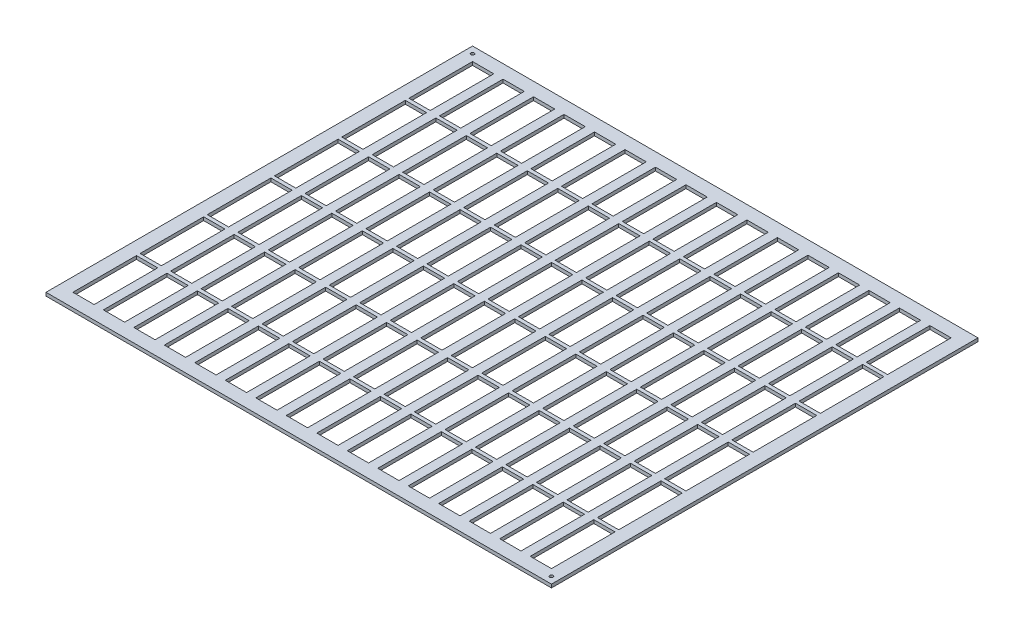
SolidWorks part; units mm, degrees
ref_plane "Front" through (0, 0, 0) normal (0, 0, 1) x (1, 0, 0)
ref_plane "Top" through (0, 0, 0) normal (0, 1, 0) x (1, 0, 0)
ref_plane "Right" through (0, 0, 0) normal (1, 0, 0) x (0, 0, -1)
sketch "Sketch1" plane through (0, 0, 0) normal (0, 1, 0) x (1, 0, 0)
  line L0 (0, -76.0537) -> (0, -227.7466) construction
  line L5 (-238.9187, -201.6125) -> (238.9188, -201.6125)
  line L6 (-238.9187, -201.6125) -> (-238.9187, 201.6125)
  line L7 (-238.9187, 201.6125) -> (238.9188, 201.6125)
  line L8 (238.9188, -201.6125) -> (238.9188, 201.6125)
  line L9 (-238.9187, -201.6125) -> (238.9188, 201.6125) construction
  line L10 (-238.9187, 201.6125) -> (238.9188, -201.6125) construction
  line L11 (55.3206, 0) -> (102.8784, 0) construction
  point P0 (0, 0)
  dimension "D1" = 477.8375
  dimension "D2" = 403.225
extrude "Boss-Extrude1" add sketch "Sketch1" along normal blind 3.175
sketch "Sketch2" plane through (0, 0, 0) normal (0, 1, 0) x (1, 0, 0)
  line L1 (-226.2187, 188.9125) -> (-206.1187, 188.9125)
  line L2 (-226.2187, 188.9125) -> (-226.2187, 128.8125)
  line L3 (-226.2187, 128.8125) -> (-206.1187, 128.8125)
  line L4 (-206.1187, 188.9125) -> (-206.1187, 128.8125)
  line L8 (206.1188, -128.8125) -> (226.2188, -128.8125) construction
  line L9 (206.1188, -128.8125) -> (206.1188, -188.9125) construction
  line L10 (206.1188, -188.9125) -> (226.2188, -188.9125) construction
  line L11 (226.2188, -128.8125) -> (226.2188, -188.9125) construction
  line L12 (-226.2187, -188.9125) -> (226.2188, -188.9125)
  line L13 (226.2188, -188.9125) -> (226.2188, 188.9125)
  line L14 (226.2188, 188.9125) -> (-226.2187, 188.9125)
  line L15 (-226.2187, 188.9125) -> (-226.2187, -188.9125)
  line L16 (-226.2187, -188.9125) -> (226.2188, -188.9125) construction
  line L17 (226.2188, -188.9125) -> (226.2188, 188.9125) construction
  line L18 (226.2188, 188.9125) -> (-226.2187, 188.9125) construction
  line L19 (-226.2187, 188.9125) -> (-226.2187, -188.9125) construction
  line L20 (216.1688, -128.8125) -> (216.1688, -188.9125) construction
  line L21 (206.1188, -158.8625) -> (226.2188, -158.8625) construction
  dimension "D1" = 60.1
  dimension "D2" = 20.1
  dimension "D3" = 12.7
extrude "Cut-Extrude1" cut sketch "Sketch2" along normal through all
pattern_linear "LPattern2" count 16 spacing 28.8225 along (1, 0, 0) count 6 spacing 63.545 along (0, 0, 1) of "Cut-Extrude1"
sketch "Sketch4" plane through (0, 0, 0) normal (0, 1, 0) x (1, 0, 0)
  line L0 (-238.9187, -201.6125) -> (238.9188, -201.6125) construction
  line L1 (238.9188, -201.6125) -> (238.9188, 201.6125) construction
  line L2 (238.9188, 201.6125) -> (-238.9187, 201.6125) construction
  line L3 (-238.9187, 201.6125) -> (-238.9187, -201.6125) construction
  circle A0 centre (-232.5687, 195.2625) radius 1.5875
  circle A1 centre (232.5688, -195.2625) radius 1.5875
  dimension "D3" = 3.175
  dimension "D6" = 3.175
  dimension "D1" = 6.35
  dimension "D2" = 6.35
  dimension "D4" = 6.35
  dimension "D5" = 6.35
extrude "Cut-Extrude2" cut sketch "Sketch4" along normal through all
sketch "v1" plane through (0, 0, 0) normal (0, 1, 0) x (1, 0, 0)
  line L0 (238.9188, -201.6125) -> (238.9188, 201.6125) construction
  line L9 (-238.9187, -201.6125) -> (238.9188, -201.6125) construction
  line L10 (-238.9187, 201.6125) -> (-238.9187, -201.6125) construction
  line L11 (238.9188, 201.6125) -> (-238.9187, 201.6125) construction
  line L12 (238.9188, -201.6125) -> (238.9188, 201.6125)
  line L13 (-238.9187, -201.6125) -> (238.9188, -201.6125)
  line L14 (-238.9187, 201.6125) -> (-238.9187, -201.6125)
  line L15 (238.9188, 201.6125) -> (-238.9187, 201.6125)
  line L16 (-206.1187, 128.8125) -> (-206.1187, 188.9125) construction
  line L17 (-206.1187, 188.9125) -> (-226.2187, 188.9125) construction
  line L18 (-226.2187, 128.8125) -> (-206.1187, 128.8125) construction
  line L19 (-226.2187, 188.9125) -> (-226.2187, 128.8125) construction
  line L20 (-226.2187, 128.8125) -> (-206.1187, 128.8125)
  line L21 (-206.1187, 188.9125) -> (-226.2187, 188.9125)
  line L22 (-206.1187, 128.8125) -> (-206.1187, 188.9125)
  line L23 (-226.2187, 188.9125) -> (-226.2187, 128.8125)
  line L24 (-180.7187, 188.9125) -> (-200.8187, 188.9125)
  line L25 (-226.2187, 188.9125) -> (-206.1187, 188.9125)
  line L26 (-226.2187, 188.9125) -> (-226.2187, 128.8125)
  line L27 (-226.2187, 128.8125) -> (-206.1187, 128.8125)
  line L28 (-206.1187, 188.9125) -> (-206.1187, 128.8125)
  line L29 (-200.8187, 188.9125) -> (-200.8187, 128.8125)
  line L30 (-200.8187, 128.8125) -> (-180.7187, 128.8125)
  line L31 (-180.7187, 128.8125) -> (-180.7187, 188.9125)
  line L32 (-155.3187, 188.9125) -> (-175.4187, 188.9125)
  line L33 (-175.4187, 188.9125) -> (-175.4187, 128.8125)
  line L34 (-175.4187, 128.8125) -> (-155.3187, 128.8125)
  line L35 (-155.3187, 128.8125) -> (-155.3187, 188.9125)
  line L36 (-129.9187, 188.9125) -> (-150.0187, 188.9125)
  line L37 (-150.0187, 188.9125) -> (-150.0187, 128.8125)
  line L38 (-150.0187, 128.8125) -> (-129.9187, 128.8125)
  line L39 (-129.9187, 128.8125) -> (-129.9187, 188.9125)
  line L40 (-104.5187, 188.9125) -> (-124.6187, 188.9125)
  line L41 (-124.6187, 188.9125) -> (-124.6187, 128.8125)
  line L42 (-124.6187, 128.8125) -> (-104.5187, 128.8125)
  line L43 (-104.5187, 128.8125) -> (-104.5187, 188.9125)
  line L44 (-79.1187, 188.9125) -> (-99.2187, 188.9125)
  line L45 (-99.2187, 188.9125) -> (-99.2187, 128.8125)
  line L46 (-99.2187, 128.8125) -> (-79.1187, 128.8125)
  line L47 (-79.1187, 128.8125) -> (-79.1187, 188.9125)
  line L48 (-53.7187, 188.9125) -> (-73.8187, 188.9125)
  line L49 (-73.8187, 188.9125) -> (-73.8187, 128.8125)
  line L50 (-73.8187, 128.8125) -> (-53.7187, 128.8125)
  line L51 (-53.7187, 128.8125) -> (-53.7187, 188.9125)
  line L52 (-28.3187, 188.9125) -> (-48.4187, 188.9125)
  line L53 (-48.4187, 188.9125) -> (-48.4187, 128.8125)
  line L54 (-48.4187, 128.8125) -> (-28.3187, 128.8125)
  line L55 (-28.3187, 128.8125) -> (-28.3187, 188.9125)
  line L56 (-2.9187, 188.9125) -> (-23.0187, 188.9125)
  line L57 (-23.0187, 188.9125) -> (-23.0187, 128.8125)
  line L58 (-23.0187, 128.8125) -> (-2.9187, 128.8125)
  line L59 (-2.9187, 128.8125) -> (-2.9187, 188.9125)
  line L60 (22.4813, 188.9125) -> (2.3813, 188.9125)
  line L61 (2.3813, 188.9125) -> (2.3813, 128.8125)
  line L62 (2.3813, 128.8125) -> (22.4813, 128.8125)
  line L63 (22.4813, 128.8125) -> (22.4813, 188.9125)
  line L64 (47.8813, 188.9125) -> (27.7813, 188.9125)
  line L65 (27.7813, 188.9125) -> (27.7813, 128.8125)
  line L66 (27.7813, 128.8125) -> (47.8813, 128.8125)
  line L67 (47.8813, 128.8125) -> (47.8813, 188.9125)
  line L68 (73.2813, 188.9125) -> (53.1813, 188.9125)
  line L69 (53.1813, 188.9125) -> (53.1813, 128.8125)
  line L70 (53.1813, 128.8125) -> (73.2813, 128.8125)
  line L71 (73.2813, 128.8125) -> (73.2813, 188.9125)
  line L72 (98.6813, 188.9125) -> (78.5813, 188.9125)
  line L73 (78.5813, 188.9125) -> (78.5813, 128.8125)
  line L74 (78.5813, 128.8125) -> (98.6813, 128.8125)
  line L75 (98.6813, 128.8125) -> (98.6813, 188.9125)
  line L76 (124.0813, 188.9125) -> (103.9813, 188.9125)
  line L77 (103.9813, 188.9125) -> (103.9813, 128.8125)
  line L78 (103.9813, 128.8125) -> (124.0813, 128.8125)
  line L79 (124.0813, 128.8125) -> (124.0813, 188.9125)
  line L80 (149.4813, 188.9125) -> (129.3813, 188.9125)
  line L81 (129.3813, 188.9125) -> (129.3813, 128.8125)
  line L82 (129.3813, 128.8125) -> (149.4813, 128.8125)
  line L83 (149.4813, 128.8125) -> (149.4813, 188.9125)
  line L84 (174.8813, 188.9125) -> (154.7813, 188.9125)
  line L85 (154.7813, 188.9125) -> (154.7813, 128.8125)
  line L86 (154.7813, 128.8125) -> (174.8813, 128.8125)
  line L87 (174.8813, 128.8125) -> (174.8813, 188.9125)
  line L88 (-180.7187, 125.4125) -> (-200.8187, 125.4125)
  line L89 (-200.8187, 125.4125) -> (-200.8187, 65.3125)
  line L90 (-200.8187, 65.3125) -> (-180.7187, 65.3125)
  line L91 (-180.7187, 65.3125) -> (-180.7187, 125.4125)
  line L92 (-155.3187, 125.4125) -> (-175.4187, 125.4125)
  line L93 (-175.4187, 125.4125) -> (-175.4187, 65.3125)
  line L94 (-175.4187, 65.3125) -> (-155.3187, 65.3125)
  line L95 (-155.3187, 65.3125) -> (-155.3187, 125.4125)
  line L96 (-129.9187, 125.4125) -> (-150.0187, 125.4125)
  line L97 (-150.0187, 125.4125) -> (-150.0187, 65.3125)
  line L98 (-150.0187, 65.3125) -> (-129.9187, 65.3125)
  line L99 (-129.9187, 65.3125) -> (-129.9187, 125.4125)
  line L100 (-104.5187, 125.4125) -> (-124.6187, 125.4125)
  line L101 (-124.6187, 125.4125) -> (-124.6187, 65.3125)
  line L102 (-124.6187, 65.3125) -> (-104.5187, 65.3125)
  line L103 (-104.5187, 65.3125) -> (-104.5187, 125.4125)
  line L104 (-79.1187, 125.4125) -> (-99.2187, 125.4125)
  line L105 (-99.2187, 125.4125) -> (-99.2187, 65.3125)
  line L106 (-99.2187, 65.3125) -> (-79.1187, 65.3125)
  line L107 (-79.1187, 65.3125) -> (-79.1187, 125.4125)
  line L108 (-53.7187, 125.4125) -> (-73.8187, 125.4125)
  line L109 (-73.8187, 125.4125) -> (-73.8187, 65.3125)
  line L110 (-73.8187, 65.3125) -> (-53.7187, 65.3125)
  line L111 (-53.7187, 65.3125) -> (-53.7187, 125.4125)
  line L112 (-28.3187, 125.4125) -> (-48.4187, 125.4125)
  line L113 (-48.4187, 125.4125) -> (-48.4187, 65.3125)
  line L114 (-48.4187, 65.3125) -> (-28.3187, 65.3125)
  line L115 (-28.3187, 65.3125) -> (-28.3187, 125.4125)
  line L116 (-2.9187, 125.4125) -> (-23.0187, 125.4125)
  line L117 (-23.0187, 125.4125) -> (-23.0187, 65.3125)
  line L118 (-23.0187, 65.3125) -> (-2.9187, 65.3125)
  line L119 (-2.9187, 65.3125) -> (-2.9187, 125.4125)
  line L120 (22.4813, 125.4125) -> (2.3813, 125.4125)
  line L121 (2.3813, 125.4125) -> (2.3813, 65.3125)
  line L122 (2.3813, 65.3125) -> (22.4813, 65.3125)
  line L123 (22.4813, 65.3125) -> (22.4813, 125.4125)
  line L124 (47.8813, 125.4125) -> (27.7813, 125.4125)
  line L125 (27.7813, 125.4125) -> (27.7813, 65.3125)
  line L126 (27.7813, 65.3125) -> (47.8813, 65.3125)
  line L127 (47.8813, 65.3125) -> (47.8813, 125.4125)
  line L128 (73.2813, 125.4125) -> (53.1813, 125.4125)
  line L129 (53.1813, 125.4125) -> (53.1813, 65.3125)
  line L130 (53.1813, 65.3125) -> (73.2813, 65.3125)
  line L131 (73.2813, 65.3125) -> (73.2813, 125.4125)
  line L132 (98.6813, 125.4125) -> (78.5813, 125.4125)
  line L133 (78.5813, 125.4125) -> (78.5813, 65.3125)
  line L134 (78.5813, 65.3125) -> (98.6813, 65.3125)
  line L135 (98.6813, 65.3125) -> (98.6813, 125.4125)
  line L136 (124.0813, 125.4125) -> (103.9813, 125.4125)
  line L137 (103.9813, 125.4125) -> (103.9813, 65.3125)
  line L138 (103.9813, 65.3125) -> (124.0813, 65.3125)
  line L139 (124.0813, 65.3125) -> (124.0813, 125.4125)
  line L140 (149.4813, 125.4125) -> (129.3813, 125.4125)
  line L141 (129.3813, 125.4125) -> (129.3813, 65.3125)
  line L142 (129.3813, 65.3125) -> (149.4813, 65.3125)
  line L143 (149.4813, 65.3125) -> (149.4813, 125.4125)
  line L144 (174.8813, 125.4125) -> (154.7813, 125.4125)
  line L145 (154.7813, 125.4125) -> (154.7813, 65.3125)
  line L146 (154.7813, 65.3125) -> (174.8813, 65.3125)
  line L147 (174.8813, 65.3125) -> (174.8813, 125.4125)
  line L148 (-180.7187, 61.9125) -> (-200.8187, 61.9125)
  line L149 (-200.8187, 61.9125) -> (-200.8187, 1.8125)
  line L150 (-200.8187, 1.8125) -> (-180.7187, 1.8125)
  line L151 (-180.7187, 1.8125) -> (-180.7187, 61.9125)
  line L152 (-155.3187, 61.9125) -> (-175.4187, 61.9125)
  line L153 (-175.4187, 61.9125) -> (-175.4187, 1.8125)
  line L154 (-175.4187, 1.8125) -> (-155.3187, 1.8125)
  line L155 (-155.3187, 1.8125) -> (-155.3187, 61.9125)
  line L156 (-129.9187, 61.9125) -> (-150.0187, 61.9125)
  line L157 (-150.0187, 61.9125) -> (-150.0187, 1.8125)
  line L158 (-150.0187, 1.8125) -> (-129.9187, 1.8125)
  line L159 (-129.9187, 1.8125) -> (-129.9187, 61.9125)
  line L160 (-104.5187, 61.9125) -> (-124.6187, 61.9125)
  line L161 (-124.6187, 61.9125) -> (-124.6187, 1.8125)
  line L162 (-124.6187, 1.8125) -> (-104.5187, 1.8125)
  line L163 (-104.5187, 1.8125) -> (-104.5187, 61.9125)
  line L164 (-79.1187, 61.9125) -> (-99.2187, 61.9125)
  line L165 (-99.2187, 61.9125) -> (-99.2187, 1.8125)
  line L166 (-99.2187, 1.8125) -> (-79.1187, 1.8125)
  line L167 (-79.1187, 1.8125) -> (-79.1187, 61.9125)
  line L168 (-53.7187, 61.9125) -> (-73.8187, 61.9125)
  line L169 (-73.8187, 61.9125) -> (-73.8187, 1.8125)
  line L170 (-73.8187, 1.8125) -> (-53.7187, 1.8125)
  line L171 (-53.7187, 1.8125) -> (-53.7187, 61.9125)
  line L172 (-28.3187, 61.9125) -> (-48.4187, 61.9125)
  line L173 (-48.4187, 61.9125) -> (-48.4187, 1.8125)
  line L174 (-48.4187, 1.8125) -> (-28.3187, 1.8125)
  line L175 (-28.3187, 1.8125) -> (-28.3187, 61.9125)
  line L176 (-2.9187, 61.9125) -> (-23.0187, 61.9125)
  line L177 (-23.0187, 61.9125) -> (-23.0187, 1.8125)
  line L178 (-23.0187, 1.8125) -> (-2.9187, 1.8125)
  line L179 (-2.9187, 1.8125) -> (-2.9187, 61.9125)
  line L180 (22.4813, 61.9125) -> (2.3813, 61.9125)
  line L181 (2.3813, 61.9125) -> (2.3813, 1.8125)
  line L182 (2.3813, 1.8125) -> (22.4813, 1.8125)
  line L183 (22.4813, 1.8125) -> (22.4813, 61.9125)
  line L184 (47.8813, 61.9125) -> (27.7813, 61.9125)
  line L185 (27.7813, 61.9125) -> (27.7813, 1.8125)
  line L186 (27.7813, 1.8125) -> (47.8813, 1.8125)
  line L187 (47.8813, 1.8125) -> (47.8813, 61.9125)
  line L188 (73.2813, 61.9125) -> (53.1813, 61.9125)
  line L189 (53.1813, 61.9125) -> (53.1813, 1.8125)
  line L190 (53.1813, 1.8125) -> (73.2813, 1.8125)
  line L191 (73.2813, 1.8125) -> (73.2813, 61.9125)
  line L192 (98.6813, 61.9125) -> (78.5813, 61.9125)
  line L193 (78.5813, 61.9125) -> (78.5813, 1.8125)
  line L194 (78.5813, 1.8125) -> (98.6813, 1.8125)
  line L195 (98.6813, 1.8125) -> (98.6813, 61.9125)
  line L196 (124.0813, 61.9125) -> (103.9813, 61.9125)
  line L197 (103.9813, 61.9125) -> (103.9813, 1.8125)
  line L198 (103.9813, 1.8125) -> (124.0813, 1.8125)
  line L199 (124.0813, 1.8125) -> (124.0813, 61.9125)
  line L200 (149.4813, 61.9125) -> (129.3813, 61.9125)
  line L201 (129.3813, 61.9125) -> (129.3813, 1.8125)
  line L202 (129.3813, 1.8125) -> (149.4813, 1.8125)
  line L203 (149.4813, 1.8125) -> (149.4813, 61.9125)
  line L204 (174.8813, 61.9125) -> (154.7813, 61.9125)
  line L205 (154.7813, 61.9125) -> (154.7813, 1.8125)
  line L206 (154.7813, 1.8125) -> (174.8813, 1.8125)
  line L207 (174.8813, 1.8125) -> (174.8813, 61.9125)
  line L208 (-180.7187, -1.5875) -> (-200.8187, -1.5875)
  line L209 (-200.8187, -1.5875) -> (-200.8187, -61.6875)
  line L210 (-200.8187, -61.6875) -> (-180.7187, -61.6875)
  line L211 (-180.7187, -61.6875) -> (-180.7187, -1.5875)
  line L212 (-155.3187, -1.5875) -> (-175.4187, -1.5875)
  line L213 (-175.4187, -1.5875) -> (-175.4187, -61.6875)
  line L214 (-175.4187, -61.6875) -> (-155.3187, -61.6875)
  line L215 (-155.3187, -61.6875) -> (-155.3187, -1.5875)
  line L216 (-129.9187, -1.5875) -> (-150.0187, -1.5875)
  line L217 (-150.0187, -1.5875) -> (-150.0187, -61.6875)
  line L218 (-150.0187, -61.6875) -> (-129.9187, -61.6875)
  line L219 (-129.9187, -61.6875) -> (-129.9187, -1.5875)
  line L220 (-104.5187, -1.5875) -> (-124.6187, -1.5875)
  line L221 (-124.6187, -1.5875) -> (-124.6187, -61.6875)
  line L222 (-124.6187, -61.6875) -> (-104.5187, -61.6875)
  line L223 (-104.5187, -61.6875) -> (-104.5187, -1.5875)
  line L224 (-79.1187, -1.5875) -> (-99.2187, -1.5875)
  line L225 (-99.2187, -1.5875) -> (-99.2187, -61.6875)
  line L226 (-99.2187, -61.6875) -> (-79.1187, -61.6875)
  line L227 (-79.1187, -61.6875) -> (-79.1187, -1.5875)
  line L228 (-53.7187, -1.5875) -> (-73.8187, -1.5875)
  line L229 (-73.8187, -1.5875) -> (-73.8187, -61.6875)
  line L230 (-73.8187, -61.6875) -> (-53.7187, -61.6875)
  line L231 (-53.7187, -61.6875) -> (-53.7187, -1.5875)
  line L232 (-28.3187, -1.5875) -> (-48.4187, -1.5875)
  line L233 (-48.4187, -1.5875) -> (-48.4187, -61.6875)
  line L234 (-48.4187, -61.6875) -> (-28.3187, -61.6875)
  line L235 (-28.3187, -61.6875) -> (-28.3187, -1.5875)
  line L236 (-2.9187, -1.5875) -> (-23.0187, -1.5875)
  line L237 (-23.0187, -1.5875) -> (-23.0187, -61.6875)
  line L238 (-23.0187, -61.6875) -> (-2.9187, -61.6875)
  line L239 (-2.9187, -61.6875) -> (-2.9187, -1.5875)
  line L240 (22.4813, -1.5875) -> (2.3813, -1.5875)
  line L241 (2.3813, -1.5875) -> (2.3813, -61.6875)
  line L242 (2.3813, -61.6875) -> (22.4813, -61.6875)
  line L243 (22.4813, -61.6875) -> (22.4813, -1.5875)
  line L244 (47.8813, -1.5875) -> (27.7813, -1.5875)
  line L245 (27.7813, -1.5875) -> (27.7813, -61.6875)
  line L246 (27.7813, -61.6875) -> (47.8813, -61.6875)
  line L247 (47.8813, -61.6875) -> (47.8813, -1.5875)
  line L248 (73.2813, -1.5875) -> (53.1813, -1.5875)
  line L249 (53.1813, -1.5875) -> (53.1813, -61.6875)
  line L250 (53.1813, -61.6875) -> (73.2813, -61.6875)
  line L251 (73.2813, -61.6875) -> (73.2813, -1.5875)
  line L252 (98.6813, -1.5875) -> (78.5813, -1.5875)
  line L253 (78.5813, -1.5875) -> (78.5813, -61.6875)
  line L254 (78.5813, -61.6875) -> (98.6813, -61.6875)
  line L255 (98.6813, -61.6875) -> (98.6813, -1.5875)
  line L256 (124.0813, -1.5875) -> (103.9813, -1.5875)
  line L257 (103.9813, -1.5875) -> (103.9813, -61.6875)
  line L258 (103.9813, -61.6875) -> (124.0813, -61.6875)
  line L259 (124.0813, -61.6875) -> (124.0813, -1.5875)
  line L260 (149.4813, -1.5875) -> (129.3813, -1.5875)
  line L261 (129.3813, -1.5875) -> (129.3813, -61.6875)
  line L262 (129.3813, -61.6875) -> (149.4813, -61.6875)
  line L263 (149.4813, -61.6875) -> (149.4813, -1.5875)
  line L264 (174.8813, -1.5875) -> (154.7813, -1.5875)
  line L265 (154.7813, -1.5875) -> (154.7813, -61.6875)
  line L266 (154.7813, -61.6875) -> (174.8813, -61.6875)
  line L267 (174.8813, -61.6875) -> (174.8813, -1.5875)
  line L268 (-180.7187, -65.0875) -> (-200.8187, -65.0875)
  line L269 (-200.8187, -65.0875) -> (-200.8187, -125.1875)
  line L270 (-200.8187, -125.1875) -> (-180.7187, -125.1875)
  line L271 (-180.7187, -125.1875) -> (-180.7187, -65.0875)
  line L272 (-155.3187, -65.0875) -> (-175.4187, -65.0875)
  line L273 (-175.4187, -65.0875) -> (-175.4187, -125.1875)
  line L274 (-175.4187, -125.1875) -> (-155.3187, -125.1875)
  line L275 (-155.3187, -125.1875) -> (-155.3187, -65.0875)
  line L276 (-129.9187, -65.0875) -> (-150.0187, -65.0875)
  line L277 (-150.0187, -65.0875) -> (-150.0187, -125.1875)
  line L278 (-150.0187, -125.1875) -> (-129.9187, -125.1875)
  line L279 (-129.9187, -125.1875) -> (-129.9187, -65.0875)
  line L280 (-104.5187, -65.0875) -> (-124.6187, -65.0875)
  line L281 (-124.6187, -65.0875) -> (-124.6187, -125.1875)
  line L282 (-124.6187, -125.1875) -> (-104.5187, -125.1875)
  line L283 (-104.5187, -125.1875) -> (-104.5187, -65.0875)
  line L284 (-79.1187, -65.0875) -> (-99.2187, -65.0875)
  line L285 (-99.2187, -65.0875) -> (-99.2187, -125.1875)
  line L286 (-99.2187, -125.1875) -> (-79.1187, -125.1875)
  line L287 (-79.1187, -125.1875) -> (-79.1187, -65.0875)
  line L288 (-53.7187, -65.0875) -> (-73.8187, -65.0875)
  line L289 (-73.8187, -65.0875) -> (-73.8187, -125.1875)
  line L290 (-73.8187, -125.1875) -> (-53.7187, -125.1875)
  line L291 (-53.7187, -125.1875) -> (-53.7187, -65.0875)
  line L292 (-28.3187, -65.0875) -> (-48.4187, -65.0875)
  line L293 (-48.4187, -65.0875) -> (-48.4187, -125.1875)
  line L294 (-48.4187, -125.1875) -> (-28.3187, -125.1875)
  line L295 (-28.3187, -125.1875) -> (-28.3187, -65.0875)
  line L296 (-2.9187, -65.0875) -> (-23.0187, -65.0875)
  line L297 (-23.0187, -65.0875) -> (-23.0187, -125.1875)
  line L298 (-23.0187, -125.1875) -> (-2.9187, -125.1875)
  line L299 (-2.9187, -125.1875) -> (-2.9187, -65.0875)
  line L300 (22.4813, -65.0875) -> (2.3813, -65.0875)
  line L301 (2.3813, -65.0875) -> (2.3813, -125.1875)
  line L302 (2.3813, -125.1875) -> (22.4813, -125.1875)
  line L303 (22.4813, -125.1875) -> (22.4813, -65.0875)
  line L304 (47.8813, -65.0875) -> (27.7813, -65.0875)
  line L305 (27.7813, -65.0875) -> (27.7813, -125.1875)
  line L306 (27.7813, -125.1875) -> (47.8813, -125.1875)
  line L307 (47.8813, -125.1875) -> (47.8813, -65.0875)
  line L308 (73.2813, -65.0875) -> (53.1813, -65.0875)
  line L309 (53.1813, -65.0875) -> (53.1813, -125.1875)
  line L310 (53.1813, -125.1875) -> (73.2813, -125.1875)
  line L311 (73.2813, -125.1875) -> (73.2813, -65.0875)
  line L312 (98.6813, -65.0875) -> (78.5813, -65.0875)
  line L313 (78.5813, -65.0875) -> (78.5813, -125.1875)
  line L314 (78.5813, -125.1875) -> (98.6813, -125.1875)
  line L315 (98.6813, -125.1875) -> (98.6813, -65.0875)
  line L316 (124.0813, -65.0875) -> (103.9813, -65.0875)
  line L317 (103.9813, -65.0875) -> (103.9813, -125.1875)
  line L318 (103.9813, -125.1875) -> (124.0813, -125.1875)
  line L319 (124.0813, -125.1875) -> (124.0813, -65.0875)
  line L320 (149.4813, -65.0875) -> (129.3813, -65.0875)
  line L321 (129.3813, -65.0875) -> (129.3813, -125.1875)
  line L322 (129.3813, -125.1875) -> (149.4813, -125.1875)
  line L323 (149.4813, -125.1875) -> (149.4813, -65.0875)
  line L324 (174.8813, -65.0875) -> (154.7813, -65.0875)
  line L325 (154.7813, -65.0875) -> (154.7813, -125.1875)
  line L326 (154.7813, -125.1875) -> (174.8813, -125.1875)
  line L327 (174.8813, -125.1875) -> (174.8813, -65.0875)
  line L328 (-180.7187, -128.5875) -> (-200.8187, -128.5875)
  line L329 (-200.8187, -128.5875) -> (-200.8187, -188.6875)
  line L330 (-200.8187, -188.6875) -> (-180.7187, -188.6875)
  line L331 (-180.7187, -188.6875) -> (-180.7187, -128.5875)
  line L332 (-155.3187, -128.5875) -> (-175.4187, -128.5875)
  line L333 (-175.4187, -128.5875) -> (-175.4187, -188.6875)
  line L334 (-175.4187, -188.6875) -> (-155.3187, -188.6875)
  line L335 (-155.3187, -188.6875) -> (-155.3187, -128.5875)
  line L336 (-129.9187, -128.5875) -> (-150.0187, -128.5875)
  line L337 (-150.0187, -128.5875) -> (-150.0187, -188.6875)
  line L338 (-150.0187, -188.6875) -> (-129.9187, -188.6875)
  line L339 (-129.9187, -188.6875) -> (-129.9187, -128.5875)
  line L340 (-104.5187, -128.5875) -> (-124.6187, -128.5875)
  line L341 (-124.6187, -128.5875) -> (-124.6187, -188.6875)
  line L342 (-124.6187, -188.6875) -> (-104.5187, -188.6875)
  line L343 (-104.5187, -188.6875) -> (-104.5187, -128.5875)
  line L344 (-79.1187, -128.5875) -> (-99.2187, -128.5875)
  line L345 (-99.2187, -128.5875) -> (-99.2187, -188.6875)
  line L346 (-99.2187, -188.6875) -> (-79.1187, -188.6875)
  line L347 (-79.1187, -188.6875) -> (-79.1187, -128.5875)
  line L348 (-53.7187, -128.5875) -> (-73.8187, -128.5875)
  line L349 (-73.8187, -128.5875) -> (-73.8187, -188.6875)
  line L350 (-73.8187, -188.6875) -> (-53.7187, -188.6875)
  line L351 (-53.7187, -188.6875) -> (-53.7187, -128.5875)
  line L352 (-28.3187, -128.5875) -> (-48.4187, -128.5875)
  line L353 (-48.4187, -128.5875) -> (-48.4187, -188.6875)
  line L354 (-48.4187, -188.6875) -> (-28.3187, -188.6875)
  line L355 (-28.3187, -188.6875) -> (-28.3187, -128.5875)
  line L356 (-2.9187, -128.5875) -> (-23.0187, -128.5875)
  line L357 (-23.0187, -128.5875) -> (-23.0187, -188.6875)
  line L358 (-23.0187, -188.6875) -> (-2.9187, -188.6875)
  line L359 (-2.9187, -188.6875) -> (-2.9187, -128.5875)
  line L360 (22.4813, -128.5875) -> (2.3813, -128.5875)
  line L361 (2.3813, -128.5875) -> (2.3813, -188.6875)
  line L362 (2.3813, -188.6875) -> (22.4813, -188.6875)
  line L363 (22.4813, -188.6875) -> (22.4813, -128.5875)
  line L364 (47.8813, -128.5875) -> (27.7813, -128.5875)
  line L365 (27.7813, -128.5875) -> (27.7813, -188.6875)
  line L366 (27.7813, -188.6875) -> (47.8813, -188.6875)
  line L367 (47.8813, -188.6875) -> (47.8813, -128.5875)
  line L368 (73.2813, -128.5875) -> (53.1813, -128.5875)
  line L369 (53.1813, -128.5875) -> (53.1813, -188.6875)
  line L370 (53.1813, -188.6875) -> (73.2813, -188.6875)
  line L371 (73.2813, -188.6875) -> (73.2813, -128.5875)
  line L372 (98.6813, -128.5875) -> (78.5813, -128.5875)
  line L373 (78.5813, -128.5875) -> (78.5813, -188.6875)
  line L374 (78.5813, -188.6875) -> (98.6813, -188.6875)
  line L375 (98.6813, -188.6875) -> (98.6813, -128.5875)
  line L376 (124.0813, -128.5875) -> (103.9813, -128.5875)
  line L377 (103.9813, -128.5875) -> (103.9813, -188.6875)
  line L378 (103.9813, -188.6875) -> (124.0813, -188.6875)
  line L379 (124.0813, -188.6875) -> (124.0813, -128.5875)
  line L380 (149.4813, -128.5875) -> (129.3813, -128.5875)
  line L381 (129.3813, -128.5875) -> (129.3813, -188.6875)
  line L382 (129.3813, -188.6875) -> (149.4813, -188.6875)
  line L383 (149.4813, -188.6875) -> (149.4813, -128.5875)
  line L384 (174.8813, -128.5875) -> (154.7813, -128.5875)
  line L385 (154.7813, -128.5875) -> (154.7813, -188.6875)
  line L386 (154.7813, -188.6875) -> (174.8813, -188.6875)
  line L387 (174.8813, -188.6875) -> (174.8813, -128.5875)
  line L388 (-206.1187, 125.4125) -> (-226.2187, 125.4125)
  line L389 (-226.2187, 125.4125) -> (-226.2187, 65.3125)
  line L390 (-226.2187, 65.3125) -> (-206.1187, 65.3125)
  line L391 (-206.1187, 65.3125) -> (-206.1187, 125.4125)
  line L392 (-206.1187, 61.9125) -> (-226.2187, 61.9125)
  line L393 (-226.2187, 61.9125) -> (-226.2187, 1.8125)
  line L394 (-226.2187, 1.8125) -> (-206.1187, 1.8125)
  line L395 (-206.1187, 1.8125) -> (-206.1187, 61.9125)
  line L396 (-206.1187, -1.5875) -> (-226.2187, -1.5875)
  line L397 (-226.2187, -1.5875) -> (-226.2187, -61.6875)
  line L398 (-226.2187, -61.6875) -> (-206.1187, -61.6875)
  line L399 (-206.1187, -61.6875) -> (-206.1187, -1.5875)
  line L400 (-206.1187, -65.0875) -> (-226.2187, -65.0875)
  line L401 (-226.2187, -65.0875) -> (-226.2187, -125.1875)
  line L402 (-226.2187, -125.1875) -> (-206.1187, -125.1875)
  line L403 (-206.1187, -125.1875) -> (-206.1187, -65.0875)
  line L404 (-206.1187, -128.5875) -> (-226.2187, -128.5875)
  line L405 (-226.2187, -128.5875) -> (-226.2187, -188.6875)
  line L406 (-226.2187, -188.6875) -> (-206.1187, -188.6875)
  line L407 (-206.1187, -188.6875) -> (-206.1187, -128.5875)
  line L408 (-206.1187, 188.9125) -> (-180.7187, 188.9125) construction
  line L409 (-206.1187, 188.9125) -> (-206.1187, 125.4125) construction
  circle A0 centre (-232.5687, 195.2625) radius 1.5875 construction
  circle A1 centre (232.5688, -195.2625) radius 1.5875 construction
  circle A2 centre (-232.5687, 195.2625) radius 1.5875
  circle A3 centre (232.5688, -195.2625) radius 1.5875
  dimension "D3" = 25.4
  dimension "D4" = 63.5
  dimension "D1" = 16
  dimension "D2" = 6
sketch "v2" plane through (0, 0, 0) normal (0, 1, 0) x (1, 0, 0)
  line L0 (-226.2187, 111.8016) -> (-206.1187, 111.8016)
  line L3 (-226.2187, 188.9125) -> (-206.1187, 188.9125)
  line L28 (238.9188, -201.6125) -> (238.9188, 201.6125)
  line L29 (238.9188, 201.6125) -> (-238.9187, 201.6125)
  line L30 (-238.9187, 201.6125) -> (-238.9187, -201.6125)
  line L31 (-238.9187, -201.6125) -> (238.9188, -201.6125)
  line L32 (238.9188, -201.6125) -> (238.9188, 201.6125)
  line L33 (238.9188, 201.6125) -> (-238.9187, 201.6125)
  line L34 (-238.9187, 201.6125) -> (-238.9187, -201.6125)
  line L35 (-238.9187, -201.6125) -> (238.9188, -201.6125)
  line L36 (-226.2187, 188.9125) -> (-226.2187, 119.9125)
  line L37 (-226.2187, 119.9125) -> (-206.1187, 119.9125)
  line L38 (-206.1187, 188.9125) -> (-206.1187, 119.9125)
  line L39 (-226.2187, 111.8016) -> (-226.2187, 42.8016)
  line L40 (-226.2187, 42.8016) -> (-206.1187, 42.8016)
  line L41 (-206.1187, 111.8016) -> (-206.1187, 42.8016)
  line L42 (-226.2187, 34.6907) -> (-206.1187, 34.6907)
  line L43 (-226.2187, 34.6907) -> (-226.2187, -34.3093)
  line L44 (-226.2187, -34.3093) -> (-206.1187, -34.3093)
  line L45 (-206.1187, 34.6907) -> (-206.1187, -34.3093)
  line L46 (-226.2187, -42.4203) -> (-206.1187, -42.4203)
  line L47 (-226.2187, -42.4203) -> (-226.2187, -111.4203)
  line L48 (-226.2187, -111.4203) -> (-206.1187, -111.4203)
  line L49 (-206.1187, -42.4203) -> (-206.1187, -111.4203)
  line L50 (-226.2187, -119.5312) -> (-206.1187, -119.5312)
  line L51 (-226.2187, -119.5312) -> (-226.2187, -188.5312)
  line L52 (-226.2187, -188.5312) -> (-206.1187, -188.5312)
  line L53 (-206.1187, -119.5312) -> (-206.1187, -188.5312)
  line L54 (-226.2187, 188.9125) -> (-226.2187, 111.8016) construction
  line L57 (-200.8187, 111.8016) -> (-180.7187, 111.8016)
  line L58 (-200.8187, 111.8016) -> (-200.8187, 42.8016)
  line L59 (-200.8187, 42.8016) -> (-180.7187, 42.8016)
  line L60 (-180.7187, 111.8016) -> (-180.7187, 42.8016)
  line L61 (-200.8187, 34.6907) -> (-180.7187, 34.6907)
  line L62 (-200.8187, 34.6907) -> (-200.8187, -34.3093)
  line L63 (-200.8187, -34.3093) -> (-180.7187, -34.3093)
  line L64 (-180.7187, 34.6907) -> (-180.7187, -34.3093)
  line L65 (-200.8187, -42.4203) -> (-180.7187, -42.4203)
  line L66 (-200.8187, -42.4203) -> (-200.8187, -111.4203)
  line L67 (-200.8187, -111.4203) -> (-180.7187, -111.4203)
  line L68 (-180.7187, -42.4203) -> (-180.7187, -111.4203)
  line L69 (-200.8187, -119.5312) -> (-180.7187, -119.5312)
  line L70 (-200.8187, -119.5312) -> (-200.8187, -188.5312)
  line L71 (-200.8187, -188.5312) -> (-180.7187, -188.5312)
  line L72 (-180.7187, -119.5312) -> (-180.7187, -188.5312)
  line L73 (-200.8187, 188.9125) -> (-200.8187, 119.9125)
  line L74 (-200.8187, 188.9125) -> (-180.7187, 188.9125)
  line L75 (-180.7187, 188.9125) -> (-180.7187, 119.9125)
  line L76 (-200.8187, 119.9125) -> (-180.7187, 119.9125)
  line L77 (-175.4187, 111.8016) -> (-155.3187, 111.8016)
  line L78 (-175.4187, 111.8016) -> (-175.4187, 42.8016)
  line L79 (-175.4187, 42.8016) -> (-155.3187, 42.8016)
  line L80 (-155.3187, 111.8016) -> (-155.3187, 42.8016)
  line L81 (-175.4187, 34.6907) -> (-155.3187, 34.6907)
  line L82 (-175.4187, 34.6907) -> (-175.4187, -34.3093)
  line L83 (-175.4187, -34.3093) -> (-155.3187, -34.3093)
  line L84 (-155.3187, 34.6907) -> (-155.3187, -34.3093)
  line L85 (-175.4187, -42.4203) -> (-155.3187, -42.4203)
  line L86 (-175.4187, -42.4203) -> (-175.4187, -111.4203)
  line L87 (-175.4187, -111.4203) -> (-155.3187, -111.4203)
  line L88 (-155.3187, -42.4203) -> (-155.3187, -111.4203)
  line L89 (-175.4187, -119.5312) -> (-155.3187, -119.5312)
  line L90 (-175.4187, -119.5312) -> (-175.4187, -188.5312)
  line L91 (-175.4187, -188.5312) -> (-155.3187, -188.5312)
  line L92 (-155.3187, -119.5312) -> (-155.3187, -188.5312)
  line L93 (-175.4187, 188.9125) -> (-175.4187, 119.9125)
  line L94 (-175.4187, 188.9125) -> (-155.3187, 188.9125)
  line L95 (-155.3187, 188.9125) -> (-155.3187, 119.9125)
  line L96 (-175.4187, 119.9125) -> (-155.3187, 119.9125)
  line L97 (-150.0187, 111.8016) -> (-129.9187, 111.8016)
  line L98 (-150.0187, 111.8016) -> (-150.0187, 42.8016)
  line L99 (-150.0187, 42.8016) -> (-129.9187, 42.8016)
  line L100 (-129.9187, 111.8016) -> (-129.9187, 42.8016)
  line L101 (-150.0187, 34.6907) -> (-129.9187, 34.6907)
  line L102 (-150.0187, 34.6907) -> (-150.0187, -34.3093)
  line L103 (-150.0187, -34.3093) -> (-129.9187, -34.3093)
  line L104 (-129.9187, 34.6907) -> (-129.9187, -34.3093)
  line L105 (-150.0187, -42.4203) -> (-129.9187, -42.4203)
  line L106 (-150.0187, -42.4203) -> (-150.0187, -111.4203)
  line L107 (-150.0187, -111.4203) -> (-129.9187, -111.4203)
  line L108 (-129.9187, -42.4203) -> (-129.9187, -111.4203)
  line L109 (-150.0187, -119.5312) -> (-129.9187, -119.5312)
  line L110 (-150.0187, -119.5312) -> (-150.0187, -188.5312)
  line L111 (-150.0187, -188.5312) -> (-129.9187, -188.5312)
  line L112 (-129.9187, -119.5312) -> (-129.9187, -188.5312)
  line L113 (-150.0187, 188.9125) -> (-150.0187, 119.9125)
  line L114 (-150.0187, 188.9125) -> (-129.9187, 188.9125)
  line L115 (-129.9187, 188.9125) -> (-129.9187, 119.9125)
  line L116 (-150.0187, 119.9125) -> (-129.9187, 119.9125)
  line L117 (-124.6187, 111.8016) -> (-104.5187, 111.8016)
  line L118 (-124.6187, 111.8016) -> (-124.6187, 42.8016)
  line L119 (-124.6187, 42.8016) -> (-104.5187, 42.8016)
  line L120 (-104.5187, 111.8016) -> (-104.5187, 42.8016)
  line L121 (-124.6187, 34.6907) -> (-104.5187, 34.6907)
  line L122 (-124.6187, 34.6907) -> (-124.6187, -34.3093)
  line L123 (-124.6187, -34.3093) -> (-104.5187, -34.3093)
  line L124 (-104.5187, 34.6907) -> (-104.5187, -34.3093)
  line L125 (-124.6187, -42.4203) -> (-104.5187, -42.4203)
  line L126 (-124.6187, -42.4203) -> (-124.6187, -111.4203)
  line L127 (-124.6187, -111.4203) -> (-104.5187, -111.4203)
  line L128 (-104.5187, -42.4203) -> (-104.5187, -111.4203)
  line L129 (-124.6187, -119.5312) -> (-104.5187, -119.5312)
  line L130 (-124.6187, -119.5312) -> (-124.6187, -188.5312)
  line L131 (-124.6187, -188.5312) -> (-104.5187, -188.5312)
  line L132 (-104.5187, -119.5312) -> (-104.5187, -188.5312)
  line L133 (-124.6187, 188.9125) -> (-124.6187, 119.9125)
  line L134 (-124.6187, 188.9125) -> (-104.5187, 188.9125)
  line L135 (-104.5187, 188.9125) -> (-104.5187, 119.9125)
  line L136 (-124.6187, 119.9125) -> (-104.5187, 119.9125)
  line L137 (-99.2187, 111.8016) -> (-79.1187, 111.8016)
  line L138 (-99.2187, 111.8016) -> (-99.2187, 42.8016)
  line L139 (-99.2187, 42.8016) -> (-79.1187, 42.8016)
  line L140 (-79.1187, 111.8016) -> (-79.1187, 42.8016)
  line L141 (-99.2187, 34.6907) -> (-79.1187, 34.6907)
  line L142 (-99.2187, 34.6907) -> (-99.2187, -34.3093)
  line L143 (-99.2187, -34.3093) -> (-79.1187, -34.3093)
  line L144 (-79.1187, 34.6907) -> (-79.1187, -34.3093)
  line L145 (-99.2187, -42.4203) -> (-79.1187, -42.4203)
  line L146 (-99.2187, -42.4203) -> (-99.2187, -111.4203)
  line L147 (-99.2187, -111.4203) -> (-79.1187, -111.4203)
  line L148 (-79.1187, -42.4203) -> (-79.1187, -111.4203)
  line L149 (-99.2187, -119.5312) -> (-79.1187, -119.5312)
  line L150 (-99.2187, -119.5312) -> (-99.2187, -188.5312)
  line L151 (-99.2187, -188.5312) -> (-79.1187, -188.5312)
  line L152 (-79.1187, -119.5312) -> (-79.1187, -188.5312)
  line L153 (-99.2187, 188.9125) -> (-99.2187, 119.9125)
  line L154 (-99.2187, 188.9125) -> (-79.1187, 188.9125)
  line L155 (-79.1187, 188.9125) -> (-79.1187, 119.9125)
  line L156 (-99.2187, 119.9125) -> (-79.1187, 119.9125)
  line L157 (-73.8187, 111.8016) -> (-53.7187, 111.8016)
  line L158 (-73.8187, 111.8016) -> (-73.8187, 42.8016)
  line L159 (-73.8187, 42.8016) -> (-53.7187, 42.8016)
  line L160 (-53.7187, 111.8016) -> (-53.7187, 42.8016)
  line L161 (-73.8187, 34.6907) -> (-53.7187, 34.6907)
  line L162 (-73.8187, 34.6907) -> (-73.8187, -34.3093)
  line L163 (-73.8187, -34.3093) -> (-53.7187, -34.3093)
  line L164 (-53.7187, 34.6907) -> (-53.7187, -34.3093)
  line L165 (-73.8187, -42.4203) -> (-53.7187, -42.4203)
  line L166 (-73.8187, -42.4203) -> (-73.8187, -111.4203)
  line L167 (-73.8187, -111.4203) -> (-53.7187, -111.4203)
  line L168 (-53.7187, -42.4203) -> (-53.7187, -111.4203)
  line L169 (-73.8187, -119.5312) -> (-53.7187, -119.5312)
  line L170 (-73.8187, -119.5312) -> (-73.8187, -188.5312)
  line L171 (-73.8187, -188.5312) -> (-53.7187, -188.5312)
  line L172 (-53.7187, -119.5312) -> (-53.7187, -188.5312)
  line L173 (-73.8187, 188.9125) -> (-73.8187, 119.9125)
  line L174 (-73.8187, 188.9125) -> (-53.7187, 188.9125)
  line L175 (-53.7187, 188.9125) -> (-53.7187, 119.9125)
  line L176 (-73.8187, 119.9125) -> (-53.7187, 119.9125)
  line L177 (-48.4187, 111.8016) -> (-28.3187, 111.8016)
  line L178 (-48.4187, 111.8016) -> (-48.4187, 42.8016)
  line L179 (-48.4187, 42.8016) -> (-28.3187, 42.8016)
  line L180 (-28.3187, 111.8016) -> (-28.3187, 42.8016)
  line L181 (-48.4187, 34.6907) -> (-28.3187, 34.6907)
  line L182 (-48.4187, 34.6907) -> (-48.4187, -34.3093)
  line L183 (-48.4187, -34.3093) -> (-28.3187, -34.3093)
  line L184 (-28.3187, 34.6907) -> (-28.3187, -34.3093)
  line L185 (-48.4187, -42.4203) -> (-28.3187, -42.4203)
  line L186 (-48.4187, -42.4203) -> (-48.4187, -111.4203)
  line L187 (-48.4187, -111.4203) -> (-28.3187, -111.4203)
  line L188 (-28.3187, -42.4203) -> (-28.3187, -111.4203)
  line L189 (-48.4187, -119.5312) -> (-28.3187, -119.5312)
  line L190 (-48.4187, -119.5312) -> (-48.4187, -188.5312)
  line L191 (-48.4187, -188.5312) -> (-28.3187, -188.5312)
  line L192 (-28.3187, -119.5312) -> (-28.3187, -188.5312)
  line L193 (-48.4187, 188.9125) -> (-48.4187, 119.9125)
  line L194 (-48.4187, 188.9125) -> (-28.3187, 188.9125)
  line L195 (-28.3187, 188.9125) -> (-28.3187, 119.9125)
  line L196 (-48.4187, 119.9125) -> (-28.3187, 119.9125)
  line L197 (-23.0187, 111.8016) -> (-2.9187, 111.8016)
  line L198 (-23.0187, 111.8016) -> (-23.0187, 42.8016)
  line L199 (-23.0187, 42.8016) -> (-2.9187, 42.8016)
  line L200 (-2.9187, 111.8016) -> (-2.9187, 42.8016)
  line L201 (-23.0187, 34.6907) -> (-2.9187, 34.6907)
  line L202 (-23.0187, 34.6907) -> (-23.0187, -34.3093)
  line L203 (-23.0187, -34.3093) -> (-2.9187, -34.3093)
  line L204 (-2.9187, 34.6907) -> (-2.9187, -34.3093)
  line L205 (-23.0187, -42.4203) -> (-2.9187, -42.4203)
  line L206 (-23.0187, -42.4203) -> (-23.0187, -111.4203)
  line L207 (-23.0187, -111.4203) -> (-2.9187, -111.4203)
  line L208 (-2.9187, -42.4203) -> (-2.9187, -111.4203)
  line L209 (-23.0187, -119.5312) -> (-2.9187, -119.5312)
  line L210 (-23.0187, -119.5312) -> (-23.0187, -188.5312)
  line L211 (-23.0187, -188.5312) -> (-2.9187, -188.5312)
  line L212 (-2.9187, -119.5312) -> (-2.9187, -188.5312)
  line L213 (-23.0187, 188.9125) -> (-23.0187, 119.9125)
  line L214 (-23.0187, 188.9125) -> (-2.9187, 188.9125)
  line L215 (-2.9187, 188.9125) -> (-2.9187, 119.9125)
  line L216 (-23.0187, 119.9125) -> (-2.9187, 119.9125)
  line L217 (2.3813, 111.8016) -> (22.4813, 111.8016)
  line L218 (2.3813, 111.8016) -> (2.3813, 42.8016)
  line L219 (2.3813, 42.8016) -> (22.4813, 42.8016)
  line L220 (22.4813, 111.8016) -> (22.4813, 42.8016)
  line L221 (2.3813, 34.6907) -> (22.4813, 34.6907)
  line L222 (2.3813, 34.6907) -> (2.3813, -34.3093)
  line L223 (2.3813, -34.3093) -> (22.4813, -34.3093)
  line L224 (22.4813, 34.6907) -> (22.4813, -34.3093)
  line L225 (2.3813, -42.4203) -> (22.4813, -42.4203)
  line L226 (2.3813, -42.4203) -> (2.3813, -111.4203)
  line L227 (2.3813, -111.4203) -> (22.4813, -111.4203)
  line L228 (22.4813, -42.4203) -> (22.4813, -111.4203)
  line L229 (2.3813, -119.5312) -> (22.4813, -119.5312)
  line L230 (2.3813, -119.5312) -> (2.3813, -188.5312)
  line L231 (2.3813, -188.5312) -> (22.4813, -188.5312)
  line L232 (22.4813, -119.5312) -> (22.4813, -188.5312)
  line L233 (2.3813, 188.9125) -> (2.3813, 119.9125)
  line L234 (2.3813, 188.9125) -> (22.4813, 188.9125)
  line L235 (22.4813, 188.9125) -> (22.4813, 119.9125)
  line L236 (2.3813, 119.9125) -> (22.4813, 119.9125)
  line L237 (27.7813, 111.8016) -> (47.8813, 111.8016)
  line L238 (27.7813, 111.8016) -> (27.7813, 42.8016)
  line L239 (27.7813, 42.8016) -> (47.8813, 42.8016)
  line L240 (47.8813, 111.8016) -> (47.8813, 42.8016)
  line L241 (27.7813, 34.6907) -> (47.8813, 34.6907)
  line L242 (27.7813, 34.6907) -> (27.7813, -34.3093)
  line L243 (27.7813, -34.3093) -> (47.8813, -34.3093)
  line L244 (47.8813, 34.6907) -> (47.8813, -34.3093)
  line L245 (27.7813, -42.4203) -> (47.8813, -42.4203)
  line L246 (27.7813, -42.4203) -> (27.7813, -111.4203)
  line L247 (27.7813, -111.4203) -> (47.8813, -111.4203)
  line L248 (47.8813, -42.4203) -> (47.8813, -111.4203)
  line L249 (27.7813, -119.5312) -> (47.8813, -119.5312)
  line L250 (27.7813, -119.5312) -> (27.7813, -188.5312)
  line L251 (27.7813, -188.5312) -> (47.8813, -188.5312)
  line L252 (47.8813, -119.5312) -> (47.8813, -188.5312)
  line L253 (27.7813, 188.9125) -> (27.7813, 119.9125)
  line L254 (27.7813, 188.9125) -> (47.8813, 188.9125)
  line L255 (47.8813, 188.9125) -> (47.8813, 119.9125)
  line L256 (27.7813, 119.9125) -> (47.8813, 119.9125)
  line L257 (53.1813, 111.8016) -> (73.2813, 111.8016)
  line L258 (53.1813, 111.8016) -> (53.1813, 42.8016)
  line L259 (53.1813, 42.8016) -> (73.2813, 42.8016)
  line L260 (73.2813, 111.8016) -> (73.2813, 42.8016)
  line L261 (53.1813, 34.6907) -> (73.2813, 34.6907)
  line L262 (53.1813, 34.6907) -> (53.1813, -34.3093)
  line L263 (53.1813, -34.3093) -> (73.2813, -34.3093)
  line L264 (73.2813, 34.6907) -> (73.2813, -34.3093)
  line L265 (53.1813, -42.4203) -> (73.2813, -42.4203)
  line L266 (53.1813, -42.4203) -> (53.1813, -111.4203)
  line L267 (53.1813, -111.4203) -> (73.2813, -111.4203)
  line L268 (73.2813, -42.4203) -> (73.2813, -111.4203)
  line L269 (53.1813, -119.5312) -> (73.2813, -119.5312)
  line L270 (53.1813, -119.5312) -> (53.1813, -188.5312)
  line L271 (53.1813, -188.5312) -> (73.2813, -188.5312)
  line L272 (73.2813, -119.5312) -> (73.2813, -188.5312)
  line L273 (53.1813, 188.9125) -> (53.1813, 119.9125)
  line L274 (53.1813, 188.9125) -> (73.2813, 188.9125)
  line L275 (73.2813, 188.9125) -> (73.2813, 119.9125)
  line L276 (53.1813, 119.9125) -> (73.2813, 119.9125)
  line L277 (78.5813, 111.8016) -> (98.6813, 111.8016)
  line L278 (78.5813, 111.8016) -> (78.5813, 42.8016)
  line L279 (78.5813, 42.8016) -> (98.6813, 42.8016)
  line L280 (98.6813, 111.8016) -> (98.6813, 42.8016)
  line L281 (78.5813, 34.6907) -> (98.6813, 34.6907)
  line L282 (78.5813, 34.6907) -> (78.5813, -34.3093)
  line L283 (78.5813, -34.3093) -> (98.6813, -34.3093)
  line L284 (98.6813, 34.6907) -> (98.6813, -34.3093)
  line L285 (78.5813, -42.4203) -> (98.6813, -42.4203)
  line L286 (78.5813, -42.4203) -> (78.5813, -111.4203)
  line L287 (78.5813, -111.4203) -> (98.6813, -111.4203)
  line L288 (98.6813, -42.4203) -> (98.6813, -111.4203)
  line L289 (78.5813, -119.5312) -> (98.6813, -119.5312)
  line L290 (78.5813, -119.5312) -> (78.5813, -188.5312)
  line L291 (78.5813, -188.5312) -> (98.6813, -188.5312)
  line L292 (98.6813, -119.5312) -> (98.6813, -188.5312)
  line L293 (78.5813, 188.9125) -> (78.5813, 119.9125)
  line L294 (78.5813, 188.9125) -> (98.6813, 188.9125)
  line L295 (98.6813, 188.9125) -> (98.6813, 119.9125)
  line L296 (78.5813, 119.9125) -> (98.6813, 119.9125)
  line L297 (103.9813, 111.8016) -> (124.0813, 111.8016)
  line L298 (103.9813, 111.8016) -> (103.9813, 42.8016)
  line L299 (103.9813, 42.8016) -> (124.0813, 42.8016)
  line L300 (124.0813, 111.8016) -> (124.0813, 42.8016)
  line L301 (103.9813, 34.6907) -> (124.0813, 34.6907)
  line L302 (103.9813, 34.6907) -> (103.9813, -34.3093)
  line L303 (103.9813, -34.3093) -> (124.0813, -34.3093)
  line L304 (124.0813, 34.6907) -> (124.0813, -34.3093)
  line L305 (103.9813, -42.4203) -> (124.0813, -42.4203)
  line L306 (103.9813, -42.4203) -> (103.9813, -111.4203)
  line L307 (103.9813, -111.4203) -> (124.0813, -111.4203)
  line L308 (124.0813, -42.4203) -> (124.0813, -111.4203)
  line L309 (103.9813, -119.5312) -> (124.0813, -119.5312)
  line L310 (103.9813, -119.5312) -> (103.9813, -188.5312)
  line L311 (103.9813, -188.5312) -> (124.0813, -188.5312)
  line L312 (124.0813, -119.5312) -> (124.0813, -188.5312)
  line L313 (103.9813, 188.9125) -> (103.9813, 119.9125)
  line L314 (103.9813, 188.9125) -> (124.0813, 188.9125)
  line L315 (124.0813, 188.9125) -> (124.0813, 119.9125)
  line L316 (103.9813, 119.9125) -> (124.0813, 119.9125)
  line L317 (129.3813, 111.8016) -> (149.4813, 111.8016)
  line L318 (129.3813, 111.8016) -> (129.3813, 42.8016)
  line L319 (129.3813, 42.8016) -> (149.4813, 42.8016)
  line L320 (149.4813, 111.8016) -> (149.4813, 42.8016)
  line L321 (129.3813, 34.6907) -> (149.4813, 34.6907)
  line L322 (129.3813, 34.6907) -> (129.3813, -34.3093)
  line L323 (129.3813, -34.3093) -> (149.4813, -34.3093)
  line L324 (149.4813, 34.6907) -> (149.4813, -34.3093)
  line L325 (129.3813, -42.4203) -> (149.4813, -42.4203)
  line L326 (129.3813, -42.4203) -> (129.3813, -111.4203)
  line L327 (129.3813, -111.4203) -> (149.4813, -111.4203)
  line L328 (149.4813, -42.4203) -> (149.4813, -111.4203)
  line L329 (129.3813, -119.5312) -> (149.4813, -119.5312)
  line L330 (129.3813, -119.5312) -> (129.3813, -188.5312)
  line L331 (129.3813, -188.5312) -> (149.4813, -188.5312)
  line L332 (149.4813, -119.5312) -> (149.4813, -188.5312)
  line L333 (129.3813, 188.9125) -> (129.3813, 119.9125)
  line L334 (129.3813, 188.9125) -> (149.4813, 188.9125)
  line L335 (149.4813, 188.9125) -> (149.4813, 119.9125)
  line L336 (129.3813, 119.9125) -> (149.4813, 119.9125)
  line L337 (154.7813, 111.8016) -> (174.8813, 111.8016)
  line L338 (154.7813, 111.8016) -> (154.7813, 42.8016)
  line L339 (154.7813, 42.8016) -> (174.8813, 42.8016)
  line L340 (174.8813, 111.8016) -> (174.8813, 42.8016)
  line L341 (154.7813, 34.6907) -> (174.8813, 34.6907)
  line L342 (154.7813, 34.6907) -> (154.7813, -34.3093)
  line L343 (154.7813, -34.3093) -> (174.8813, -34.3093)
  line L344 (174.8813, 34.6907) -> (174.8813, -34.3093)
  line L345 (154.7813, -42.4203) -> (174.8813, -42.4203)
  line L346 (154.7813, -42.4203) -> (154.7813, -111.4203)
  line L347 (154.7813, -111.4203) -> (174.8813, -111.4203)
  line L348 (174.8813, -42.4203) -> (174.8813, -111.4203)
  line L349 (154.7813, -119.5312) -> (174.8813, -119.5312)
  line L350 (154.7813, -119.5312) -> (154.7813, -188.5312)
  line L351 (154.7813, -188.5312) -> (174.8813, -188.5312)
  line L352 (174.8813, -119.5312) -> (174.8813, -188.5312)
  line L353 (154.7813, 188.9125) -> (154.7813, 119.9125)
  line L354 (154.7813, 188.9125) -> (174.8813, 188.9125)
  line L355 (174.8813, 188.9125) -> (174.8813, 119.9125)
  line L356 (154.7813, 119.9125) -> (174.8813, 119.9125)
  line L397 (-226.2187, 111.8016) -> (-200.8187, 111.8016) construction
  circle A1 centre (232.5688, -195.2625) radius 1.5875
  circle A2 centre (232.5688, -195.2625) radius 1.5875
  circle A3 centre (-232.5687, 195.2625) radius 1.5875
  circle A4 centre (-232.5687, 195.2625) radius 1.5875
  point P0 (-226.2187, 188.9125)
  dimension "D3" = 69
  dimension "D4" = 20.1
  dimension "D7" = 77.1109
  dimension "D9" = 25.4
  dimension "D1" = 0
  dimension "D2" = 0
  dimension "D5" = 5
  dimension "D6" = 0
  dimension "D8" = 16
